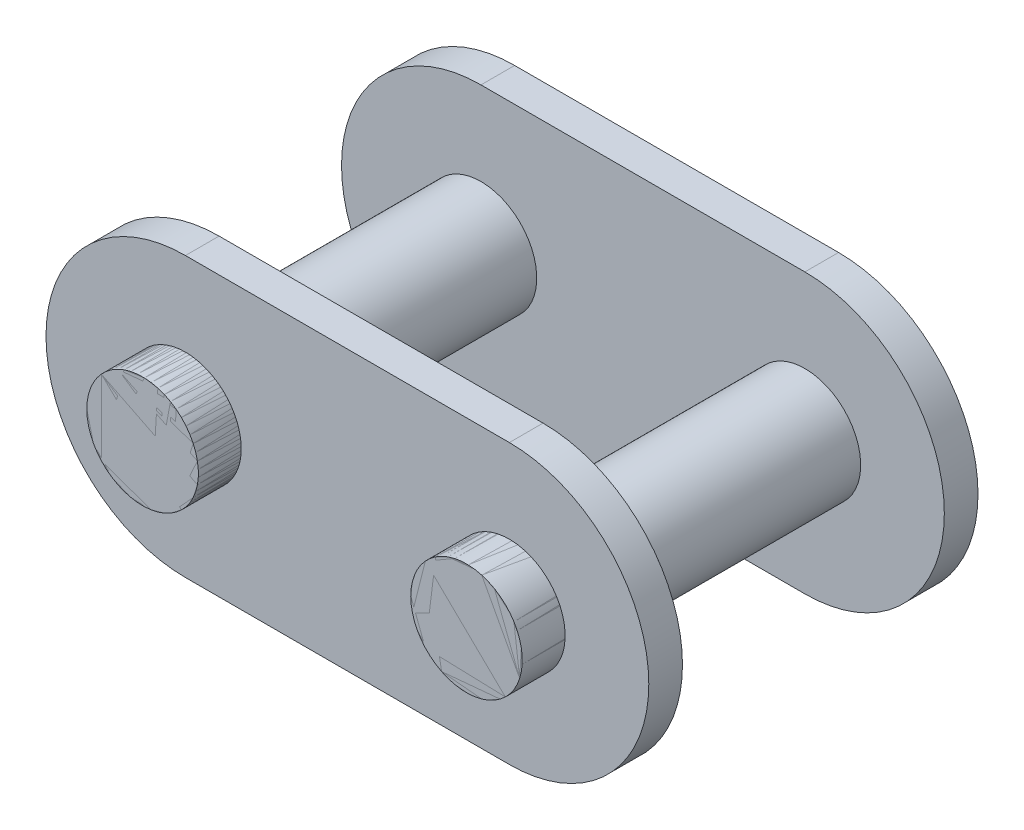
SolidWorks part; units mm, degrees
material "AISI 304"
ref_plane "Plane1" through (0, 0, 0) normal (0, 0, 1) x (1, 0, 0)
ref_plane "Plane2" through (0, 0, 0) normal (0, 1, 0) x (1, 0, 0)
ref_plane "Plane3" through (0, 0, 0) normal (1, 0, 0) x (0, 0, -1)
sketch "Sketch1" plane through (0, 0, 0) normal (0, 0, 1) x (1, 0, 0)
  line L0 (4.7625, 4.1) -> (4.7625, -4.1) construction
  line L1 (0, 4.1) -> (9.525, 4.1)
  line L2 (0, -4.1) -> (9.525, -4.1)
  arc A0 (0, 4.1) -> (0, -4.1) centre (0, 0) ccw
  circle A4 centre (0, 0) radius 1.64
  circle A8 centre (9.525, 0) radius 1.64
  arc A9 (9.525, 4.1) -> (9.525, -4.1) centre (9.525, 0) cw
  point P10 (3.175, 4.1)
  point P11 (3.175, -4.1)
  point P13 (0, 0)
  point P14 (0, 0)
  dimension "D1" = 8.2
  dimension "D2" = 4.7625
  dimension "D6" = 3.28
extrude "Boss-Extrude1" add sketch "Sketch1" along normal blind 0.99
sketch "Sketch2" plane through (0, 0, 0) normal (0, 0, -1) x (-1, 0, 0)
  circle A0 centre (-9.525, 0) radius 1.64
  circle A1 centre (0, 0) radius 1.64
  dimension "D1" = 3.28
  dimension "D2" = 3.28
extrude "Boss-Extrude2" add sketch "Sketch2" along normal blind 9.95 and the other way blind 2.25
ref_plane "Plane4" through (0, 0, -3.85) normal (0, 0, -1) x (-1, 0, 0)
mirror "Mirror1" about plane through (0, 0, -3.85) normal (0, 0, -1) of bodies 105 104
